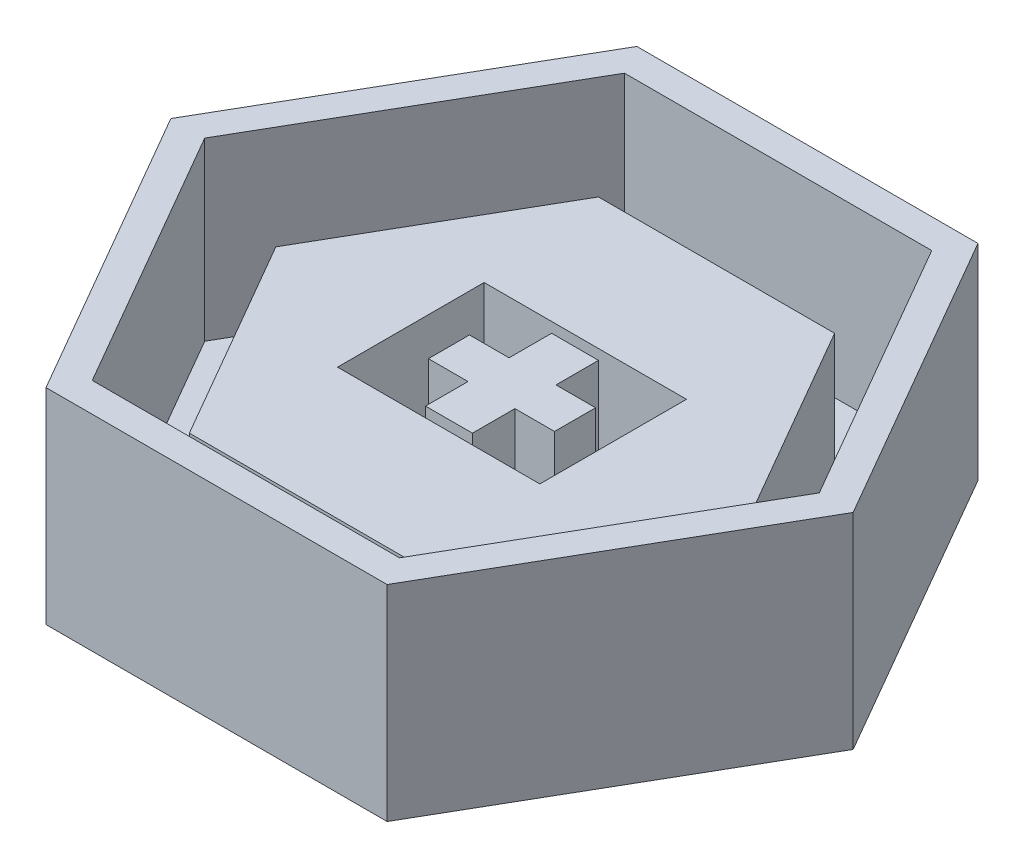
SolidWorks part; units mm, degrees
ref_plane "Plan de face" through (0, 0, 0) normal (0, 0, 1) x (1, 0, 0)
ref_plane "Plan de dessus" through (0, 0, 0) normal (0, 1, 0) x (1, 0, 0)
ref_plane "Plan de droite" through (0, 0, 0) normal (1, 0, 0) x (0, 0, -1)
sketch "Sketch1" plane through (0, 0, 0) normal (0, 1, 0) x (1, 0, 0)
  line L0 (0, 2.15) -> (0, -2.15) construction
  line L1 (-2.15, 0) -> (2.15, 0) construction
  line L2 (-0.8, 2.15) -> (0.8, 2.15)
  line L3 (0.8, 2.15) -> (0.8, 0.7)
  line L4 (0.8, 0.7) -> (2.15, 0.7)
  line L5 (2.15, 0.7) -> (2.15, -0.7)
  line L6 (2.15, -0.7) -> (0.8, -0.7)
  line L7 (0.8, -0.7) -> (0.8, -2.15)
  line L8 (0.8, -2.15) -> (-0.8, -2.15)
  line L9 (-0.8, -2.15) -> (-0.8, -0.7)
  line L10 (-0.8, -0.7) -> (-2.15, -0.7)
  line L11 (-2.15, -0.7) -> (-2.15, 0.7)
  line L12 (-2.15, 0.7) -> (-0.8, 0.7)
  line L13 (-0.8, 0.7) -> (-0.8, 2.15)
  point P17 (1.9456, 0.5786)
  point P18 (0.65, 1.6959)
  dimension "D1" = 1.6
  dimension "D2" = 1.4
  dimension "D3" = 4.3
extrude "Cross" add sketch "Sketch1" along normal blind 4
sketch "Sketch3" plane through (0, 0, 0) normal (0, -1, 0) x (1, 0, 0)
  line L0 (0, 0) -> (10.4789, 0) construction
  line L1 (10.4789, 0) -> (5.2395, 9.075)
  line L2 (5.2395, 9.075) -> (-5.2395, 9.075)
  line L3 (-5.2395, 9.075) -> (-10.4789, 0)
  line L4 (-10.4789, 0) -> (-5.2395, -9.075)
  line L5 (-5.2395, -9.075) -> (5.2395, -9.075)
  line L6 (5.2395, -9.075) -> (10.4789, 0)
  circle A0 centre (0, 0) radius 9.075 construction
  dimension "D1" = 18.15
extrude "Bottom" add sketch "Sketch3" along normal blind 1
sketch "Sketch4" plane through (0, 0, 0) normal (0, -1, 0) x (1, 0, 0)
  line L0 (5.8168, -10.075) -> (11.6336, 0)
  line L1 (11.6336, 0) -> (5.8168, 10.075)
  line L2 (5.8168, 10.075) -> (-5.8168, 10.075)
  line L3 (-5.8168, 10.075) -> (-11.6336, 0)
  line L4 (-11.6336, 0) -> (-5.8168, -10.075)
  line L5 (-5.8168, -10.075) -> (5.8168, -10.075)
  line L6 (5.2395, -9.075) -> (10.4789, 0)
  line L7 (10.4789, 0) -> (5.2395, 9.075)
  line L8 (5.2395, 9.075) -> (-5.2395, 9.075)
  line L9 (-5.2395, 9.075) -> (-10.4789, 0)
  line L10 (-10.4789, 0) -> (-5.2395, -9.075)
  line L11 (-5.2395, -9.075) -> (5.2395, -9.075)
  line L12 (5.2395, -9.075) -> (10.4789, 0)
  line L13 (10.4789, 0) -> (5.2395, 9.075)
  line L14 (5.2395, 9.075) -> (-5.2395, 9.075)
  line L15 (-5.2395, 9.075) -> (-10.4789, 0)
  line L16 (-10.4789, 0) -> (-5.2395, -9.075)
  line L17 (-5.2395, -9.075) -> (5.2395, -9.075)
  dimension "D1" = 0
  dimension "D2" = 1
extrude "Walls" add sketch "Sketch4" against normal blind 6 and the other way up to surface (1 mm away) other way up to face at (0, -1, 0)
sketch "Sketch5" plane through (0, 0, 0) normal (0, 1, 0) x (1, 0, 0)
  line L0 (0, 0) -> (8.054, 0) construction
  line L1 (3.45, 2.5) -> (-3.45, 2.5)
  line L2 (3.45, 2.5) -> (3.45, -2.5)
  line L3 (3.45, -2.5) -> (-3.45, -2.5)
  line L4 (-3.45, 2.5) -> (-3.45, -2.5)
  line L5 (3.45, 2.5) -> (-3.45, -2.5) construction
  line L6 (3.45, -2.5) -> (-3.45, 2.5) construction
  line L7 (8.054, 0) -> (4.027, 6.975)
  line L8 (4.027, 6.975) -> (-4.027, 6.975)
  line L9 (-4.027, 6.975) -> (-8.054, 0)
  line L10 (-8.054, 0) -> (-4.027, -6.975)
  line L11 (-4.027, -6.975) -> (4.027, -6.975)
  line L12 (4.027, -6.975) -> (8.054, 0)
  line L13 (-5.2395, 9.075) -> (5.2395, 9.075) construction
  circle A0 centre (0, 0) radius 6.975 construction
  point P0 (0, 0)
  dimension "D1" = 5
  dimension "D2" = 6.9
  dimension "D3" = 2.1
extrude "Boss-Extrude4" add sketch "Sketch5" along normal offset from surface (4 mm away) 2 up to face at (0, 6, 0)
equation "\"offset_cross\"= 0.1mm"
equation "\"D1@Sketch1\"=1.50+\"offset_cross\""
equation "\"D2@Sketch1\"=1.30+\"offset_cross\""
equation "\"D3@Sketch1\"=4.20+\"offset_cross\""
equation "\"square_offset\"= 0.1mm"
equation "\"s\" = 18.05mm"
equation "\"walls_offset\"= 0.1mm"
equation "\"D1@Sketch3\"=\"s\"+\"walls_offset\""
equation "\"height\" = 6mm"
equation "\"D1@Walls\" = \"height\""
equation "\"D1@Sketch5\"=4.9+\"square_offset\""
equation "\"D2@Sketch5\"=6.8+\"square_offset\""
equation "\"sides\" = 2mm"
equation "\"D3@Sketch5\"=\"sides\"+\"walls_offset\""
equation "\"top_thickness\"= 2mm"
equation "\"D1@Boss-Extrude4\"=\"top_thickness\""
